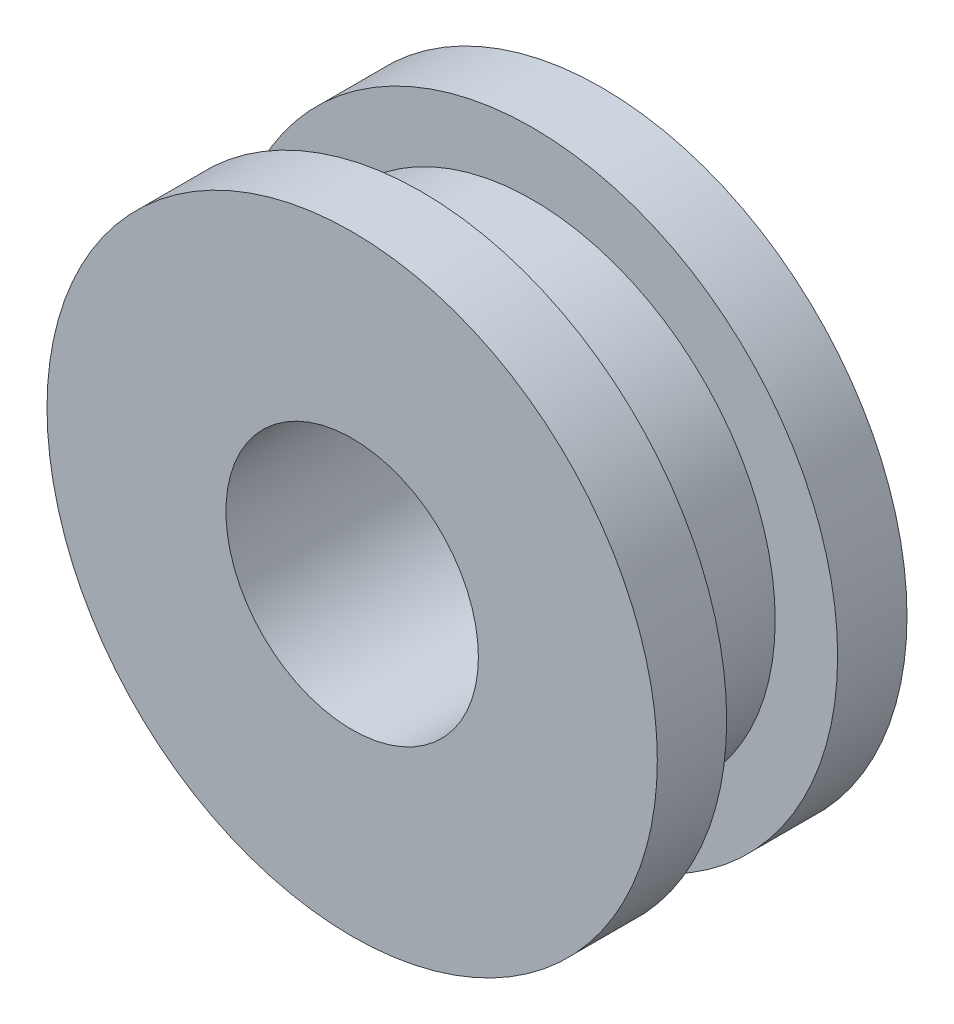
SolidWorks part; units mm, degrees
material "Rubber"
ref_plane "Front Plane" through (0, 0, 0) normal (0, 0, 1) x (1, 0, 0)
ref_plane "Top Plane" through (0, 0, 0) normal (0, 1, 0) x (1, 0, 0)
ref_plane "Right Plane" through (0, 0, 0) normal (1, 0, 0) x (0, 0, -1)
sketch "Sketch1" plane through (0, 0, 0) normal (1, 0, 0) x (0, 0, -1)
  line L0 (-4.5, 11) -> (-2, 11)
  line L1 (-2, 11) -> (-2, 8.75)
  line L2 (-2, 8.75) -> (2, 8.75)
  line L3 (2, 8.75) -> (2, 11)
  line L4 (2, 11) -> (4.5, 11)
  line L5 (4.5, 11) -> (4.5, 4.55)
  line L6 (4.5, 4.55) -> (-4.5, 4.55)
  line L7 (-4.5, 4.55) -> (-4.5, 11)
  line L8 (0, 44.2539) -> (0, -44.2539) construction
  line L9 (55, 0) -> (-55, 0) construction
  line L10 (-12.3295, 0) -> (10.5111, 0) construction
  dimension "D1" = 4
  dimension "D2" = 9
  dimension "D3" = 4.5
  dimension "D4" = 4.55
  dimension "D5" = 11
  dimension "D6" = 8.75
revolve "Revolve1" add sketch "Sketch1" angle 360 about L10
equation "\"InnerThick\"=4"
equation "\"D1@Sketch1\"=\"InnerThick\""
equation "\"OuterThick\"=9"
equation "\"D2@Sketch1\"=\"OuterThick\""
equation "\"D3@Sketch1\"=\"OuterThick\"/2"
equation "\"InnerDiam\"=4.55"
equation "\"D4@Sketch1\"=\"InnerDiam\""
equation "\"OuterRad\"=11"
equation "\"D5@Sketch1\"=\"OuterRad\""
equation "\"RingRad\"=8.75"
equation "\"D6@Sketch1\"=\"RingRad\""
